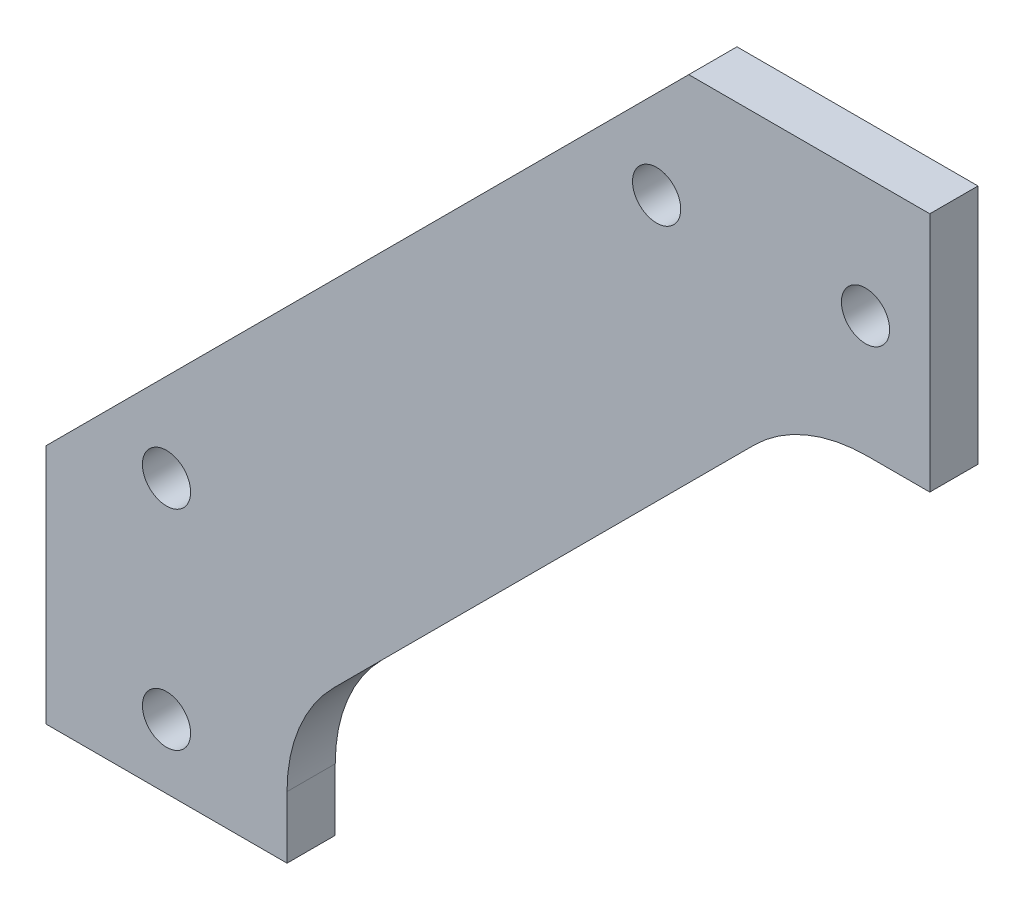
SolidWorks part; units mm, degrees
ref_plane "前视基准面" through (0, 0, 0) normal (0, 0, 1) x (1, 0, 0)
ref_plane "上视基准面" through (0, 0, 0) normal (0, 1, 0) x (1, 0, 0)
ref_plane "右视基准面" through (0, 0, 0) normal (1, 0, 0) x (0, 0, -1)
sketch "草图1" plane through (0, 0, 0) normal (0, 0, 1) x (1, 0, 0)
  line L0 (0, 0) -> (15, 0)
  line L1 (15, 0) -> (15, -15)
  line L2 (15, -15) -> (11.1421, -15)
  line L3 (4.0711, -17.9289) -> (-22.0711, -44.0711)
  line L4 (-25, -51.1421) -> (-25, -55)
  line L5 (-25, -55) -> (-40, -55)
  line L6 (-40, -55) -> (-40, -40)
  line L7 (-40, -40) -> (0, 0)
  arc A0 (11.1421, -15) -> (4.0711, -17.9289) centre (11.1421, -25) ccw
  arc A1 (-22.0711, -44.0711) -> (-25, -51.1421) centre (-15, -51.1421) ccw
  point P11 (7, -15)
  point P14 (-25, -47)
  dimension "D9" = 10
  dimension "D1" = 15
  dimension "D2" = 15
  dimension "D3" = 8
  dimension "D4" = 8
  dimension "D5" = 15
  dimension "D6" = 15
  dimension "D7" = 135
  dimension "D8" = 40
extrude "凸台-拉伸1" add sketch "草图1" along normal blind 3
sketch "草图2" plane through (0, 0, 3) normal (0, 0, 1) x (1, 0, 0)
  line L0 (15, 0) -> (0, 0) construction
  line L1 (-40, -40) -> (-40, -55) construction
  line L2 (15, -15) -> (15, 0) construction
  line L3 (-40, -55) -> (-25, -55) construction
  circle A0 centre (11, -7.5) radius 1.5
  circle A1 centre (-2, -7.5) radius 1.5
  circle A2 centre (-32.5, -51) radius 1.5
  circle A3 centre (-32.5, -38) radius 1.5
  point P12 (0, 0)
  point P13 (0, 0)
  dimension "D1" = 3
  dimension "D2" = 7.5
  dimension "D3" = 7.5
  dimension "D4" = 4
  dimension "D5" = 13
  dimension "D6" = 4
  dimension "D7" = 13
extrude "切除-拉伸1" cut sketch "草图2" against normal blind 3
